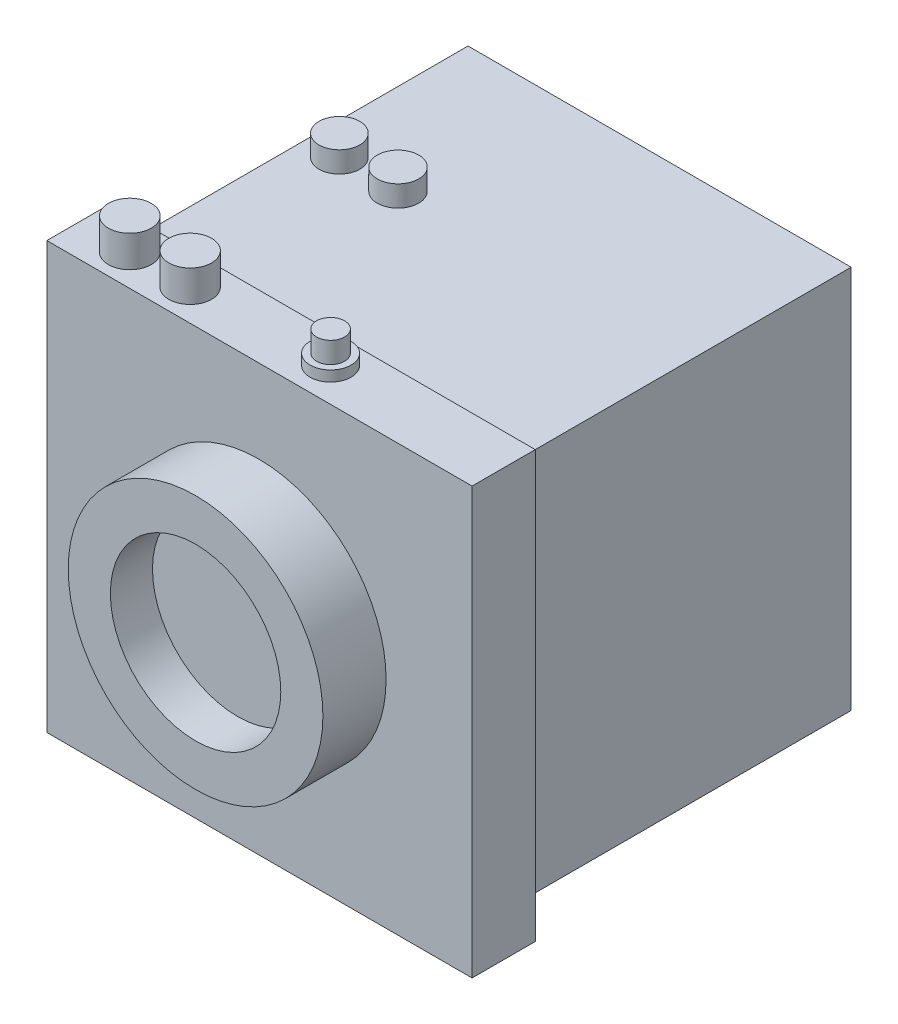
SolidWorks part; units mm, degrees
ref_plane "Front Plane" through (0, 0, 0) normal (0, 0, 1) x (1, 0, 0)
ref_plane "Top Plane" through (0, 0, 0) normal (0, 1, 0) x (1, 0, 0)
ref_plane "Right Plane" through (0, 0, 0) normal (1, 0, 0) x (0, 0, -1)
sketch "Sketch1" plane through (0, 0, 0) normal (0, 0, 1) x (1, 0, 0)
  line L1 (-30.1494, 28.1842) -> (21.1382, 28.1842)
  line L2 (-30.1494, 28.1842) -> (-30.1494, -23.1992)
  line L3 (-30.1494, -23.1992) -> (21.1382, -23.1992)
  line L4 (21.1382, 28.1842) -> (21.1382, -23.1992)
  dimension "D1" = 51.2876
  dimension "D2" = 51.3835
extrude "Boss-Extrude1" add sketch "Sketch1" along normal blind 7.62
shell "Shell2" thickness 2.54
sketch "Sketch3" plane through (0, 0, 5.08) normal (0, 0, -1) x (-1, 0, 0)
  line L1 (-18.5982, 25.6442) -> (27.6094, 25.6442)
  line L2 (-18.5982, 25.6442) -> (-18.5982, -20.6592)
  line L3 (-18.5982, -20.6592) -> (27.6094, -20.6592)
  line L4 (27.6094, 25.6442) -> (27.6094, -20.6592)
extrude "Boss-Extrude2" add sketch "Sketch3" along normal blind 45.72 separate body
sketch "Sketch8" plane through (0, 0, 7.62) normal (0, 0, 1) x (1, 0, 0)
  line L0 (21.1382, 28.1842) -> (-30.1494, 28.1842) construction
  circle A0 centre (-4.591, 2.7842) radius 15.3566
  dimension "D1" = 25.4
extrude "Boss-Extrude4" add sketch "Sketch8" along normal blind 7.62
shell "Shell9" thickness 5.08
sketch "Sketch11" plane through (0, 28.1842, 0) normal (0, 1, 0) x (1, 0, 0)
  circle A0 centre (-23.9248, -3.8352) radius 2.5898
  circle A1 centre (-16.6467, -3.8352) radius 2.5766
  dimension "D1" = 5.1533
  dimension "D2" = 5.1795
extrude "Boss-Extrude5" add sketch "Sketch11" along normal blind 3.81
sketch "Sketch12" plane through (0, 28.1842, 0) normal (0, 1, 0) x (1, 0, 0)
  circle A0 centre (0, -3.5465) radius 2.4749
extrude "Boss-Extrude6" add sketch "Sketch12" along normal blind 1.27
sketch "Sketch13" plane through (0, 29.4542, 0) normal (0, 1, 0) x (1, 0, 0)
  circle A0 centre (0, -3.5465) radius 1.689
extrude "Boss-Extrude7" add sketch "Sketch13" along normal blind 2.54
sketch "Sketch16" plane through (0, 25.6442, 0) normal (0, 1, 0) x (1, 0, 0)
  circle A0 centre (-16.659, 21.2409) radius 2.4967
  circle A1 centre (-23.7266, 21.2409) radius 2.4628
  dimension "D1" = 4.9256
  dimension "D2" = 4.9934
extrude "Boss-Extrude9" add sketch "Sketch16" along normal blind 2.54
